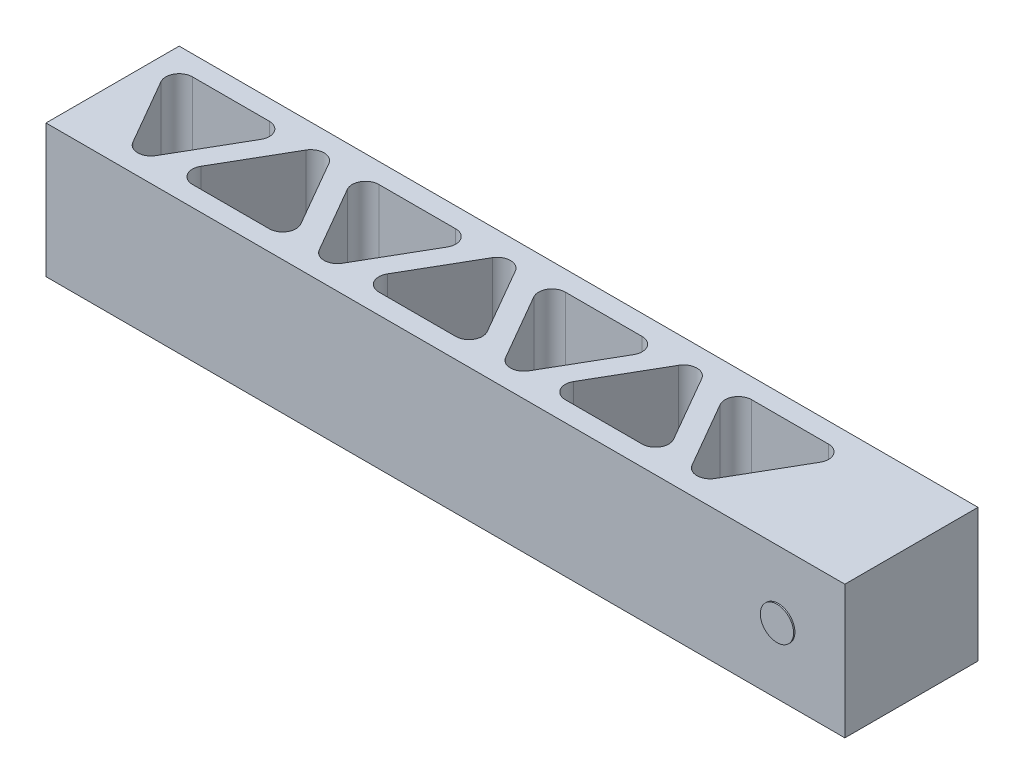
SolidWorks part; units mm, degrees
ref_plane "Front Plane" through (0, 0, 0) normal (0, 0, 1) x (1, 0, 0)
ref_plane "Top Plane" through (0, 0, 0) normal (0, 1, 0) x (1, 0, 0)
ref_plane "Right Plane" through (0, 0, 0) normal (1, 0, 0) x (0, 0, -1)
sketch "Sketch5" plane through (0, 0, 0) normal (0, 0, 1) x (1, 0, 0)
  line L0 (120, 0) -> (120, 20)
  line L1 (0, 0) -> (120, 0)
  line L2 (0, 0) -> (0, 20)
  line L3 (0, 20) -> (120, 20)
  dimension "D1" = 20
  dimension "D2" = 120
extrude "Boss-Extrude1" add sketch "Sketch5" along normal blind 20
sketch "Sketch7" plane through (0, 20, 0) normal (0, 1, 0) x (1, 0, 0)
  line L1 (0, -10) -> (120, -10) construction
  line L2 (0, -20) -> (0, 0) construction
  line L3 (120, -20) -> (120, 0) construction
  line L4 (120, 0) -> (100, -20) construction
  line L5 (120, -20) -> (0, -20) construction
  circle A1 centre (110, -10) radius 2.5
  dimension "D1" = 5
  dimension "D2" = 45
extrude "Boss-Extrude2" add sketch "Sketch7" along normal blind 0.2 and the other way offset from surface (20.2 mm away) 0.2 other way up to face at (60, 0, 10)
sketch "Sketch6" plane through (0, 0, 20) normal (0, 0, 1) x (1, 0, 0)
  line L0 (54.5056, 4) -> (60.2791, 14)
  line L9 (5, 3) -> (16.547, 3)
  line L10 (18.2791, 6) -> (12.5056, 16)
  line L11 (3, 3) -> (120, 3)
  line L12 (3, 17) -> (3, 3)
  line L13 (120, 17) -> (3, 17)
  line L14 (3, 3) -> (120, 3) construction
  line L15 (3, 17) -> (3, 3) construction
  line L16 (120, 17) -> (3, 17) construction
  line L17 (9.0415, 16) -> (3.2679, 6)
  line L18 (26.5056, 4) -> (32.2791, 14)
  line L19 (30.547, 17) -> (19, 17)
  line L20 (17.2679, 14) -> (23.0415, 4)
  line L21 (37.0415, 16) -> (31.2679, 6)
  line L22 (33, 3) -> (44.547, 3)
  line L23 (46.2791, 6) -> (40.5056, 16)
  line L24 (65.0415, 16) -> (59.2679, 6)
  line L25 (61, 3) -> (72.547, 3)
  line L26 (74.2791, 6) -> (68.5056, 16)
  line L27 (93.0415, 16) -> (87.2679, 6)
  line L28 (89, 3) -> (100.547, 3)
  line L29 (102.2791, 6) -> (96.5056, 16)
  line L33 (120, 0) -> (120, 20) construction
  line L34 (58.547, 17) -> (47, 17)
  line L35 (45.2679, 14) -> (51.0415, 4)
  line L36 (82.5056, 4) -> (88.2791, 14)
  line L37 (86.547, 17) -> (75, 17)
  line L38 (73.2679, 14) -> (79.0415, 4)
  arc A0 (16.547, 3) -> (18.2791, 6) centre (16.547, 5) ccw
  arc A1 (5, 3) -> (3.2679, 6) centre (5, 5) cw
  arc A2 (9.0415, 16) -> (12.5056, 16) centre (10.7735, 15) cw
  arc A3 (19, 17) -> (17.2679, 14) centre (19, 15) ccw
  arc A4 (30.547, 17) -> (32.2791, 14) centre (30.547, 15) cw
  arc A5 (26.5056, 4) -> (23.0415, 4) centre (24.7735, 5) cw
  arc A6 (37.0415, 16) -> (40.5056, 16) centre (38.7735, 15) cw
  arc A7 (33, 3) -> (31.2679, 6) centre (33, 5) cw
  arc A8 (44.547, 3) -> (46.2791, 6) centre (44.547, 5) ccw
  arc A9 (65.0415, 16) -> (68.5056, 16) centre (66.7735, 15) cw
  arc A10 (61, 3) -> (59.2679, 6) centre (61, 5) cw
  arc A11 (72.547, 3) -> (74.2791, 6) centre (72.547, 5) ccw
  arc A12 (93.0415, 16) -> (96.5056, 16) centre (94.7735, 15) cw
  arc A13 (89, 3) -> (87.2679, 6) centre (89, 5) cw
  arc A14 (100.547, 3) -> (102.2791, 6) centre (100.547, 5) ccw
  arc A18 (58.547, 17) -> (60.2791, 14) centre (58.547, 15) cw
  arc A19 (47, 17) -> (45.2679, 14) centre (47, 15) ccw
  arc A20 (54.5056, 4) -> (51.0415, 4) centre (52.7735, 5) cw
  arc A21 (86.547, 17) -> (88.2791, 14) centre (86.547, 15) cw
  arc A22 (75, 17) -> (73.2679, 14) centre (75, 15) ccw
  arc A23 (82.5056, 4) -> (79.0415, 4) centre (80.7735, 5) cw
  point P1 (52.7735, 17)
  point P9 (10.7735, 3)
  point P13 (20.0111, 3)
  point P16 (1.5359, 3)
  point P23 (10.7735, 19)
  point P24 (24.7735, 17)
  point P71 (38.7735, 3)
  point P159 (5.0538, 5)
  point P160 (10.7735, 17)
  dimension "D3" = 2
  dimension "D2" = 3
  dimension "D4" = 4
  dimension "D5" = 14
  dimension "D6" = 28
  dimension "D7" = 28
  dimension "D1" = 3
extrude "Cut-Extrude1" cut sketch "Sketch6" against normal through all
move or copy body "Body-Move/Copy1" bodies to move or copy 102 copy no rotation origin (0, 7.5, 7.5) rotation axis (1, 0, 0) rotation angle 90
